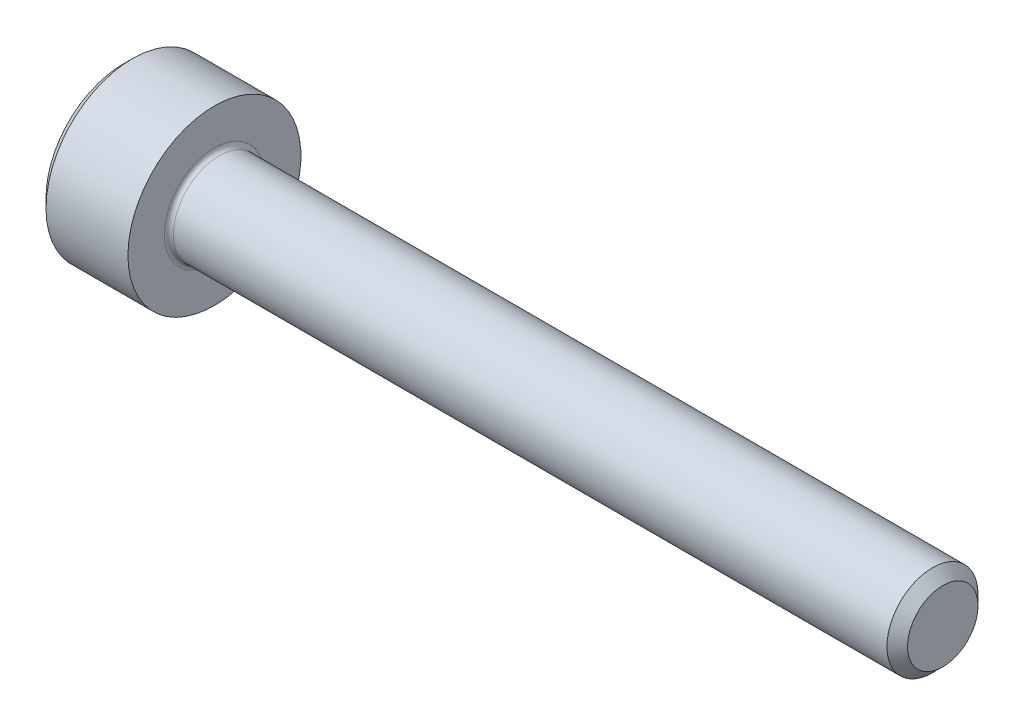
SolidWorks part; units mm, degrees
revolve "Base-Revolve" add sketch "BodySke"
sketch "BodySke" plane through (0, 0, 0) normal (0, 0, 1) x (1, 0, 0)
  line L0 (0, 0) -> (0, 1.7)
  line L1 (0.2, 1.9) -> (2, 1.9)
  line L2 (2, 1.9) -> (2, 1)
  line L3 (2, 1) -> (17.774, 1)
  line L4 (18, 0.774) -> (18, 0)
  line L5 (18, 0) -> (0, 0)
  line L6 (-31.75, 0) -> (127, 0) construction
  line L7 (0, 1.7) -> (0.2, 1.9)
  line L8 (18, 0.774) -> (17.774, 1)
  line L9 (0, -1.7) -> (0.2, -1.9) construction
  line L10 (18, -0.774) -> (17.774, -1) construction
  line L11 (2.4, 9.525) -> (2.4, 3.175) construction
  line L12 (4, 9.525) -> (4, 3.175) construction
  line L13 (-30, 9.525) -> (-30, 3.175) construction
  dimension "Diameter" = 2
  dimension "Head_ht" = 2
  dimension "Length" = 16
  dimension "Body_ch_ang" = 45
  dimension "Head_dia" = 3.8
  dimension "Head_ch_ang" = 45
  dimension "Minor_dia" = 1.548
  dimension "Advance" = 0.4
  dimension "Thread_nom" = 14
  dimension "Thread_length" = 48
  dimension "Head_ch_ht" = 0.2
cosmetic thread "ThreadCosmetic" [suppressed]
fillet "Fillet1" radius 0.1 1 edges at (2, 0, 1)
ref_plane "Plane1" through (0, 0, 0) normal (0, 0, 1) x (1, 0, 0)
ref_plane "Plane2" through (0, 0, 0) normal (0, 1, 0) x (1, 0, 0)
ref_plane "Plane3" through (0, 0, 0) normal (1, 0, 0) x (0, 0, -1)
other "Configuration Table"
sketch "Sketch2" plane through (0, 0, 0) normal (0, 0, 1) x (1, 0, 0)
  line L0 (0, 0.7725) -> (1, 0.7725)
  line L1 (1, 0.7725) -> (1.446, 0)
  line L2 (-31.75, 0) -> (127, 0) construction
  line L3 (1.446, 0) -> (0, 0)
  line L4 (0, 0) -> (0, 0.7725)
  line L5 (0, 1.7) -> (0, -1.7) construction
  line L6 (0, 0) -> (47.625, 0) construction
  line L7 (2, -1.9) -> (2, 1.9) construction
  dimension "D1" = 0.7725
  dimension "D2" = 60
revolve "Hex-PreBroach" cut sketch "Sketch2" angle 360 about L6
sketch "Sketch3" plane through (0, 0, 0) normal (-1, 0, 0) x (0, 0.5, 0.866)
  line L0 (0.446, 0.7725) -> (-0.446, 0.7725)
  line L1 (-0.446, 0.7725) -> (-0.892, 0)
  line L2 (0.446, 0.7725) -> (0.892, 0)
  line L3 (0.446, -0.7725) -> (0.892, 0)
  line L4 (0.446, -0.7725) -> (-0.446, -0.7725)
  line L5 (-0.446, -0.7725) -> (-0.892, 0)
  dimension "D1" = 0.7725
  dimension "D2" = 0.7725
  dimension "Hex_size" = 1.545
extrude "Hex" cut sketch "Sketch3" against normal blind 1
sketch "Sketch4" plane through (0, 0, 0) normal (-1, 0, 0) x (0, 0, 1)
  line L0 (0, 0) -> (0.9398, 0)
  line L1 (0, 0) -> (6.1484, 3.5498) construction
  line L2 (0, 0) -> (0.4699, 0.8139)
  line L3 (0.7832, 0.2175) -> (0.8962, 0.2828)
  line L4 (0.58, 0.5695) -> (0.693, 0.6348)
  arc A0 (0.7832, 0.2175) -> (0.58, 0.5695) centre (0, 0) ccw
  arc A1 (0.9398, 0) -> (0.8962, 0.2828) centre (0, 0) ccw
  arc A2 (0.4699, 0.8139) -> (0.693, 0.6348) centre (0, 0) cw
  dimension "D1" = 30
  dimension "D2" = 60
  dimension "Spline_p_dim" = 0.4064
  dimension "D3" = 0.2032
extrude "Spline" [suppressed] cut sketch "Sketch4" against normal blind 1
pattern_circular "CirPattern1" [suppressed] count 6 every 60
sketch "Sketch5" plane through (0, 0, 0) normal (0, 0, 1) x (1, 0, 0)
  line L0 (-31.75, 0) -> (127, 0) construction
  line L2 (0, 1.7) -> (0, -1.7) construction
  circle A0 centre (0.1, 0) radius 0.005
  dimension "Drilled_hole_dia" = 0.01
  dimension "Drilled_hole_loc" = 0.1
extrude "Hole" [suppressed] cut sketch "Sketch5" against normal through all and the other way through all
pattern_circular "Drilled-4" [suppressed] count 2 every 60
pattern_circular "Drilled-6" [suppressed] count 3 every 60
sketch "ThdSchSke" plane through (0, 0, 0) normal (0, 0, 1) x (1, 0, 0)
  line L0 (4, -0.774) -> (3.8418, -1)
  line L1 (4, -0.774) -> (4.1582, -1)
  line L2 (4.1582, -1) -> (4.1582, -1.25)
  line L3 (-3.175, 0) -> (5.1513, 0) construction
  line L5 (4.1582, -1.25) -> (3.8418, -1.25)
  line L6 (3.8418, -1.25) -> (3.8418, -1)
  line L7 (0, 1.7) -> (0, -1.7) construction
  dimension "Thread_minor" = 1.548
  dimension "Diameter" = 2
  dimension "Start" = 4
revolve "ThreadSchematic" [suppressed] cut sketch "ThdSchSke" angle 360 about L3
pattern_linear "ThdSchPat" [suppressed]
equation "\"D2@Sketch3\" = \"Hex_size@Sketch3\" / 2"
equation "\"D1@Sketch3\" = \"Hex_size@Sketch3\" / 2"
equation "\"D1@Sketch2\" = \"Hex_size@Sketch3\" / 2"
equation "\"D3@Sketch4\" = \"Spline_p_dim@Sketch4\" / 2"
equation "\"Thread_minor@ThreadCosmetic\"  =  \"Minor_dia@BodySke\""
equation "\"D2@CirPattern1\" = 360 / \"Num_teeth@CirPattern1\""
equation "\"Wall_thickness@Sketch2\" = \"Head_ht@BodySke\" - \"Key_eng@Hex\""
equation "\"Thread_length@ThreadCosmetic\" = ((sgn( (\"Length@BodySke\" - \"Advance@BodySke\" ) - \"Thread_nom@BodySke\" )-1)*( (\"Length@BodySke\" - \"Advance@BodySke\" ) - \"Thread_nom@BodySke\" ))/-2+ \"Thread_nom@BodySke\""
equation "\"Thread_minor@ThdSchSke\" = \"Minor_dia@BodySke\""
equation "\"Diameter@ThdSchSke\" = \"Diameter@BodySke\""
equation "\"Overcut@ThdSchSke\" = \"Diameter@BodySke\" * 1.25"
equation "\"Start@ThdSchSke\" = \"Head_ht@BodySke\" + \"Length@BodySke\" - \"Thread_length@ThreadCosmetic\"  '---Non-countersunk---"
equation "\"Num_threads@ThdSchPat\" = int( \"Thread_length@ThreadCosmetic\" / \"Advance@BodySke\" + 0.999 )  + 1"
equation "\"Advance@ThdSchPat\" = \"Thread_length@ThreadCosmetic\" /  (\"Num_threads@ThdSchPat\" - 1) 'relax it"
equation "\"Num_threads@ThdSchPat\" = \"Num_threads@ThdSchPat\" - sgn( \"Num_threads@ThdSchPat\" - 1) '---chamfered tips only---"
